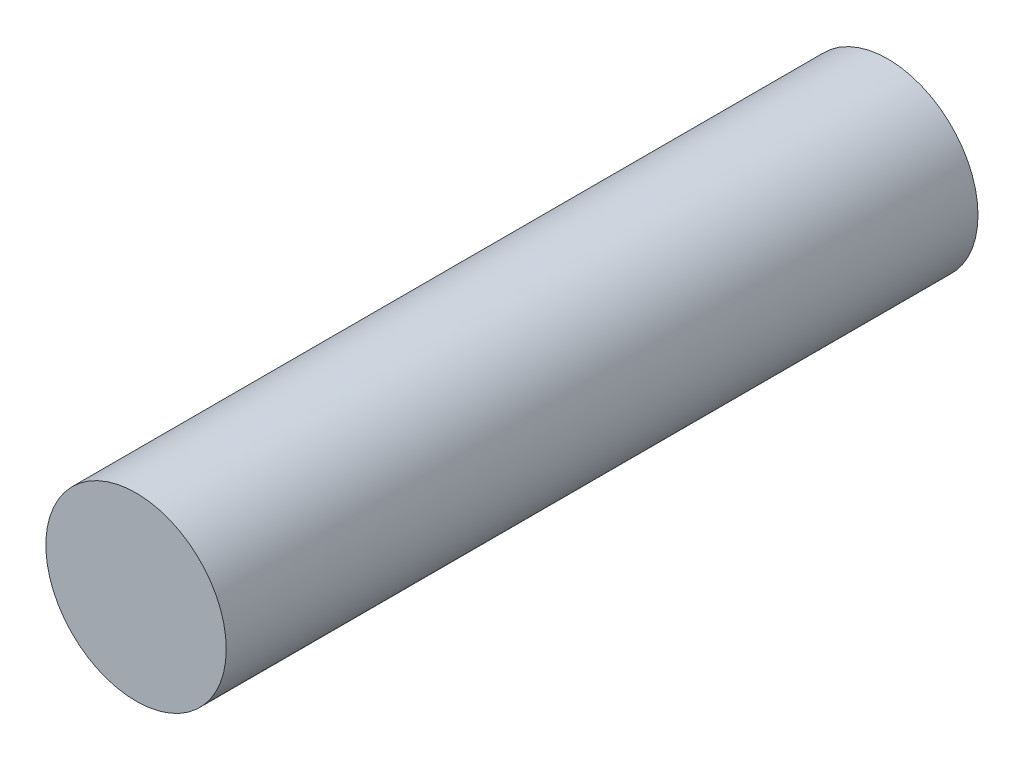
SolidWorks part; units mm, degrees
material "Alliage 1060"
ref_plane "Plan de face" through (0, 0, 0) normal (0, 0, 1) x (1, 0, 0)
ref_plane "Plan de dessus" through (0, 0, 0) normal (0, 1, 0) x (1, 0, 0)
ref_plane "Plan de droite" through (0, 0, 0) normal (1, 0, 0) x (0, 0, -1)
sketch "Esquisse2" plane through (0, 0, 0) normal (0, 0, 1) x (1, 0, 0)
  circle A0 centre (0, 0) radius 6
extrude "Boss.-Extru.1" add sketch "Esquisse2" along normal blind 50
